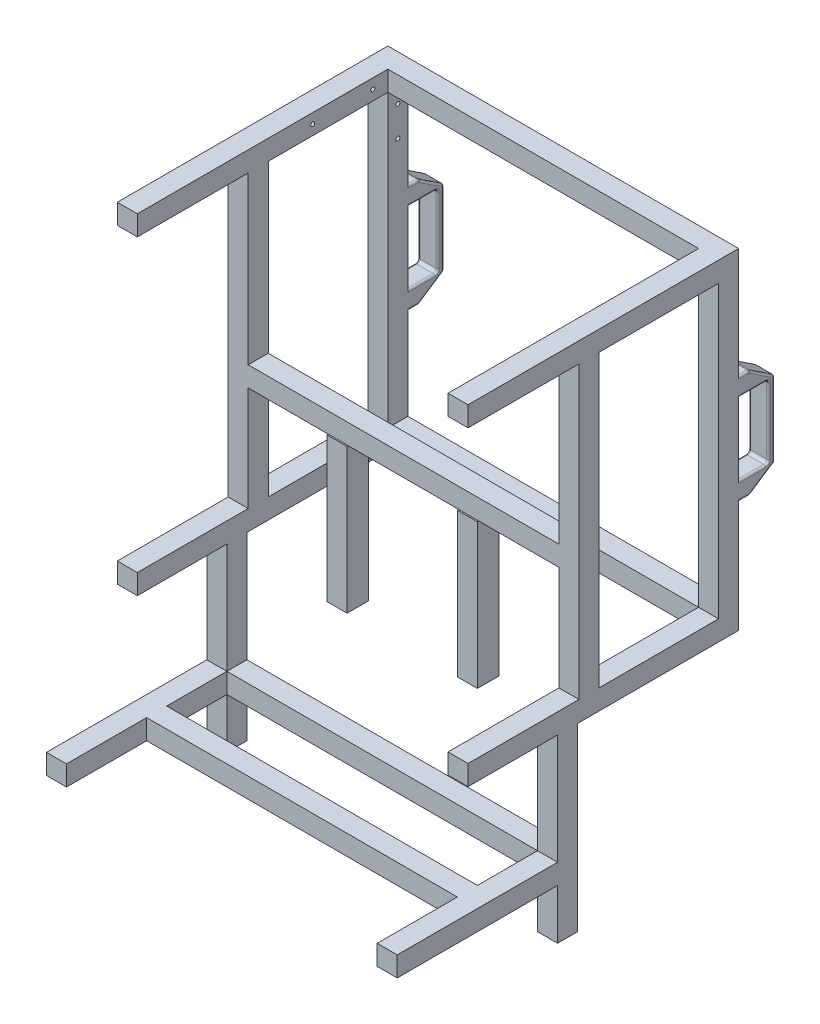
SolidWorks part; units mm, degrees
ref_plane "前视基准面" through (0, 0, 0) normal (0, 0, 1) x (1, 0, 0)
ref_plane "上视基准面" through (0, 0, 0) normal (0, 1, 0) x (1, 0, 0)
ref_plane "右视基准面" through (0, 0, 0) normal (1, 0, 0) x (0, 0, -1)
sketch "草图1" plane through (0, 0, 0) normal (0, 0, 1) x (1, 0, 0)
  line L1 (0, 0) -> (350, 0)
  line L2 (0, 0) -> (0, 330)
  line L3 (0, 330) -> (350, 330)
  line L4 (350, 0) -> (350, 330)
  line L5 (20, 310) -> (330, 310)
  line L6 (20, 310) -> (20, 20)
  line L7 (20, 20) -> (330, 20)
  line L8 (330, 310) -> (330, 20)
  dimension "D1" = 20
  dimension "D2" = 20
  dimension "D3" = 20
  dimension "D4" = 20
  dimension "D5" = 350
  dimension "D6" = 330
extrude "凸台-拉伸1" add sketch "草图1" along normal blind 20
sketch "草图2" plane through (0, 0, 20) normal (0, 0, 1) x (1, 0, 0)
  line L1 (0, 330) -> (20, 330)
  line L2 (0, 330) -> (0, 310)
  line L3 (0, 310) -> (20, 310)
  line L4 (20, 330) -> (20, 310)
  line L5 (350, 330) -> (330, 330)
  line L6 (350, 330) -> (350, 310)
  line L7 (350, 310) -> (330, 310)
  line L8 (330, 330) -> (330, 310)
  line L9 (20, 20) -> (0, 20)
  line L10 (20, 20) -> (20, 0)
  line L11 (20, 0) -> (0, 0)
  line L12 (0, 20) -> (0, 0)
  line L13 (330, 20) -> (350, 20)
  line L14 (330, 20) -> (330, 0)
  line L15 (330, 0) -> (350, 0)
  line L16 (350, 20) -> (350, 0)
extrude "凸台-拉伸2" add sketch "草图2" along normal blind 250
sketch "草图4" plane through (0, 0, 0) normal (-1, 0, 0) x (0, 0, 1)
  line L0 (0, 219) -> (0, 201)
  line L1 (0, 330) -> (0, 0) construction
  line L2 (0, 201) -> (-27, 201)
  line L3 (-30, 198) -> (-30, 132)
  line L4 (-27, 129) -> (0, 129)
  line L5 (0, 129) -> (0, 111)
  line L6 (0, 111) -> (-10.0992, 111)
  line L7 (-11.7518, 111.4962) -> (-34.6525, 126.6107)
  line L8 (-36, 129.1145) -> (-36, 200.8855)
  line L9 (-34.6525, 203.3893) -> (-11.7518, 218.5038)
  line L10 (-10.0992, 219) -> (0, 219)
  arc A0 (-10.0992, 111) -> (-11.7518, 111.4962) centre (-10.0992, 114) cw
  arc A1 (-11.7518, 218.5038) -> (-10.0992, 219) centre (-10.0992, 216) cw
  arc A2 (-36, 200.8855) -> (-34.6525, 203.3893) centre (-33, 200.8855) cw
  arc A3 (-34.6525, 126.6107) -> (-36, 129.1145) centre (-33, 129.1145) cw
  arc A4 (-30, 132) -> (-27, 129) centre (-27, 132) ccw
  arc A5 (-27, 201) -> (-30, 198) centre (-27, 198) ccw
  point P14 (-36, 165)
  point P15 (-30, 165)
  point P16 (0, 165)
  point P21 (-11, 219)
  point P24 (-36, 202.5)
  point P27 (-36, 127.5)
  point P30 (-30, 129)
  point P33 (-30, 201)
  dimension "D7" = 3
  dimension "D1" = 72
  dimension "D2" = 108
  dimension "D3" = 30
  dimension "D4" = 6
  dimension "D5" = 75
  dimension "D6" = 11
extrude "凸台-拉伸3" add sketch "草图4" against normal blind 20
sketch "草图5" plane through (350, 0, 0) normal (1, 0, 0) x (0, 0, -1)
  line L0 (27, 201) -> (0, 201) construction
  line L1 (30, 132) -> (30, 198) construction
  line L2 (0, 129) -> (27, 129) construction
  line L4 (30, 132) -> (30, 198)
  line L5 (0, 129) -> (27, 129)
  line L7 (27, 201) -> (0, 201)
  line L8 (0, 219) -> (0, 201)
  line L9 (0, 129) -> (0, 111)
  line L10 (10.0992, 219) -> (0, 219)
  line L11 (0, 219) -> (0, 310)
  line L12 (0, 310) -> (-20, 310)
  line L13 (-20, 310) -> (-20, 20)
  line L14 (-20, 20) -> (0, 20)
  line L15 (0, 20) -> (0, 111)
  line L16 (0, 111) -> (10.0992, 111)
  line L17 (11.7518, 111.4962) -> (34.6525, 126.6107)
  line L18 (36, 129.1145) -> (36, 200.8855)
  line L19 (34.6525, 203.3893) -> (11.7518, 218.5038)
  line L20 (10.0992, 219) -> (0, 219)
  line L26 (0, 111) -> (10.0992, 111)
  line L27 (11.7518, 111.4962) -> (34.6525, 126.6107)
  line L28 (36, 129.1145) -> (36, 200.8855)
  line L29 (34.6525, 203.3893) -> (11.7518, 218.5038)
  arc A0 (27, 129) -> (30, 132) centre (27, 132) ccw construction
  arc A1 (30, 198) -> (27, 201) centre (27, 198) ccw construction
  arc A2 (27, 129) -> (30, 132) centre (27, 132) ccw
  arc A3 (30, 198) -> (27, 201) centre (27, 198) ccw
  arc A4 (10.0992, 111) -> (11.7518, 111.4962) centre (10.0992, 114) ccw
  arc A5 (34.6525, 126.6107) -> (36, 129.1145) centre (33, 129.1145) ccw
  arc A6 (36, 200.8855) -> (34.6525, 203.3893) centre (33, 200.8855) ccw
  arc A7 (11.7518, 218.5038) -> (10.0992, 219) centre (10.0992, 216) ccw
  arc A8 (10.0992, 111) -> (11.7518, 111.4962) centre (10.0992, 114) ccw
  arc A9 (34.6525, 126.6107) -> (36, 129.1145) centre (33, 129.1145) ccw
  arc A10 (36, 200.8855) -> (34.6525, 203.3893) centre (33, 200.8855) ccw
  arc A11 (11.7518, 218.5038) -> (10.0992, 219) centre (10.0992, 216) ccw
  dimension "D1" = 0
extrude "凸台-拉伸4" add sketch "草图5" against normal blind 20
fillet "圆角2" radius 2 56 edges at (20, 129, -13.5) (20, 129.8787, -29.1213) (20, 201, -13.5) (20, 200.1213, -29.1213) (20, 219, -5.0496) (20, 218.8733, -10.962) (20, 210.9466, -23.2022) (20, 202.3072, -35.6417) (20, 111, -5.0496) (20, 111.1267, -10.962) (20, 119.0534, -23.2022) (20, 127.6928, -35.6417) (0, 129, -13.5) (0, 129.8787, -29.1213) (0, 201, -13.5) (0, 200.1213, -29.1213) (0, 219, -5.0496) (0, 218.8733, -10.962) (0, 210.9466, -23.2022) (0, 202.3072, -35.6417) (0, 111, -5.0496) (0, 111.1267, -10.962) (0, 119.0534, -23.2022) (0, 127.6928, -35.6417) (350, 201, -13.5) (330, 201, -13.5) (350, 200.1213, -29.1213) (330, 200.1213, -29.1213) (350, 129, -13.5) (330, 129, -13.5) (350, 129.8787, -29.1213) (330, 129.8787, -29.1213) (350, 111, -5.0496) (330, 111, -5.0496) (350, 111.1267, -10.962) (330, 111.1267, -10.962) (350, 119.0534, -23.2022) (330, 119.0534, -23.2022) (350, 127.6928, -35.6417) (330, 127.6928, -35.6417) (350, 219, -5.0496) (330, 219, -5.0496) (350, 218.8733, -10.962) (330, 218.8733, -10.962) (350, 210.9466, -23.2022) (330, 210.9466, -23.2022) (350, 202.3072, -35.6417) (330, 202.3072, -35.6417) (20, 165, -30) (20, 165, -36) (0, 165, -30) (0, 165, -36) (350, 165, -30) (330, 165, -30) (350, 165, -36) (330, 165, -36)
sketch "草图6" plane through (0, 0, 0) normal (-1, 0, 0) x (0, 0, 1)
  circle A0 centre (10, 295) radius 2
  circle A1 centre (10, 265) radius 2
  circle A2 centre (35, 320) radius 2
  circle A3 centre (95, 320) radius 2
  dimension "D1" = 4
extrude "切除-拉伸1" cut sketch "草图6" against normal blind 20
sketch "草图7" plane through (0, 0, 0) normal (0, -1, 0) x (1, 0, 0)
  line L0 (350, 270) -> (350, 0) construction
  line L1 (350, 180.6654) -> (330, 180.6654)
  line L2 (350, 180.6654) -> (350, 160.6654)
  line L3 (350, 160.6654) -> (330, 160.6654)
  line L4 (330, 180.6654) -> (330, 160.6654)
  line L5 (330, 270) -> (330, 20) construction
  line L6 (20, 270) -> (20, 20) construction
  line L7 (20, 180.6654) -> (0, 180.6654)
  line L8 (20, 180.6654) -> (20, 160.6654)
  line L9 (20, 160.6654) -> (0, 160.6654)
  line L10 (0, 180.6654) -> (0, 160.6654)
  line L11 (0, 270) -> (0, 0) construction
  dimension "D1" = 20
  dimension "D2" = 20
extrude "凸台-拉伸5" add sketch "草图7" along normal blind 180
sketch "草图8" plane through (330, 0, 0) normal (-1, 0, 0) x (0, 0, 1)
  line L0 (180.6654, -180) -> (180.6654, 0) construction
  line L1 (180.6654, -130) -> (160.6654, -130)
  line L2 (180.6654, -130) -> (180.6654, -110)
  line L3 (180.6654, -110) -> (160.6654, -110)
  line L4 (160.6654, -130) -> (160.6654, -110)
  line L5 (160.6654, -180) -> (160.6654, 0) construction
  line L6 (180.6654, -180) -> (160.6654, -180) construction
  dimension "D1" = 20
  dimension "D2" = 50
extrude "凸台-拉伸6" add sketch "草图8" along normal up to next
sketch "草图9" plane through (0, 0, 180.6654) normal (0, 0, 1) x (1, 0, 0)
  line L0 (0, -180) -> (0, 0) construction
  line L1 (20, -130) -> (0, -130)
  line L2 (20, -130) -> (20, -110)
  line L3 (20, -110) -> (0, -110)
  line L4 (0, -130) -> (0, -110)
  line L5 (350, -180) -> (350, 0) construction
  line L6 (330, -130) -> (350, -130)
  line L7 (330, -130) -> (330, -110)
  line L8 (330, -110) -> (350, -110)
  line L9 (350, -130) -> (350, -110)
extrude "凸台-拉伸7" add sketch "草图9" along normal blind 160
ref_plane "基准面1" through (175, 0, 0) normal (1, 0, 0) x (0, 0, -1)
sketch "草图10" plane through (330, 0, 0) normal (-1, 0, 0) x (0, 0, 1)
  line L0 (340.6654, -130) -> (180.6654, -130) construction
  line L1 (240.6654, -130) -> (260.6654, -130)
  line L2 (240.6654, -130) -> (240.6654, -110)
  line L3 (240.6654, -110) -> (260.6654, -110)
  line L4 (260.6654, -130) -> (260.6654, -110)
  line L5 (340.6654, -110) -> (180.6654, -110) construction
  point P8 (240.6654, -130)
  point P9 (240.6654, -130)
  dimension "D1" = 20
extrude "凸台-拉伸8" add sketch "草图10" along normal up to next
sketch "草图11" plane through (350, 0, 0) normal (1, 0, 0) x (0, 0, -1)
  line L0 (-290.6654, -145.6267) -> (-280.6654, -145.6267)
  line L1 (-340.6654, -130) -> (-280.6654, -130)
  line L2 (-340.6654, -130) -> (-340.6654, -145.6267)
  line L3 (-340.6654, -145.6267) -> (-330.6654, -145.6267)
  line L4 (-280.6654, -130) -> (-280.6654, -145.6267)
  line L5 (-295.6654, -130) -> (-325.6654, -130)
  line L6 (-290.6654, -145.6267) -> (-290.6654, -165)
  line L7 (-290.6654, -165) -> (-330.6654, -165)
  line L8 (-330.6654, -145.6267) -> (-330.6654, -165)
  circle A0 centre (-310.6654, -150) radius 12.5
  dimension "D5" = 25
  dimension "D1" = 60
  dimension "D2" = 40
  dimension "D3" = 10
  dimension "D4" = 35
  dimension "D6" = 20
sketch "草图12" plane through (0, 20, 0) normal (0, 1, 0) x (1, 0, 0)
  line L0 (350, -270) -> (350, -20) construction
  line L1 (350, -159.336) -> (330, -159.336)
  line L2 (350, -159.336) -> (350, -139.336)
  line L3 (350, -139.336) -> (330, -139.336)
  line L4 (330, -159.336) -> (330, -139.336)
  line L5 (330, -270) -> (330, -20) construction
  dimension "D1" = 20
extrude "凸台-拉伸9" add sketch "草图12" along normal up to next
mirror "镜向1" about plane through (175, 0, 0) normal (1, 0, 0) of "凸台-拉伸9"
sketch "草图13" plane through (20, 0, 0) normal (1, 0, 0) x (0, 0, -1)
  line L0 (-159.336, 310) -> (-159.336, 20) construction
  line L1 (-159.336, 144.1993) -> (-139.336, 144.1993)
  line L2 (-159.336, 144.1993) -> (-159.336, 124.1993)
  line L3 (-159.336, 124.1993) -> (-139.336, 124.1993)
  line L4 (-139.336, 144.1993) -> (-139.336, 124.1993)
  line L5 (-139.336, 310) -> (-139.336, 20) construction
  dimension "D1" = 20
extrude "凸台-拉伸10" add sketch "草图13" along normal up to next
sketch "草图14" plane through (0, 124.1993, 0) normal (0, -1, 0) x (1, 0, 0)
  line L0 (330, 139.336) -> (20, 139.336) construction
  line L1 (250, 139.336) -> (230, 139.336)
  line L2 (250, 139.336) -> (250, 160.6654)
  line L3 (250, 160.6654) -> (230, 160.6654)
  line L4 (230, 139.336) -> (230, 160.6654)
  line L5 (20, 160.6654) -> (330, 160.6654) construction
  line L6 (330, 160.6654) -> (330, 20) construction
  line L7 (120, 139.336) -> (100, 139.336)
  line L8 (120, 139.336) -> (120, 160.6654)
  line L9 (120, 160.6654) -> (100, 160.6654)
  line L10 (100, 139.336) -> (100, 160.6654)
  line L11 (20, 160.6654) -> (20, 20) construction
  dimension "D1" = 20
  dimension "D2" = 20
  dimension "D3" = 80
  dimension "D4" = 80
extrude "凸台-拉伸11" add sketch "草图14" along normal blind 144
